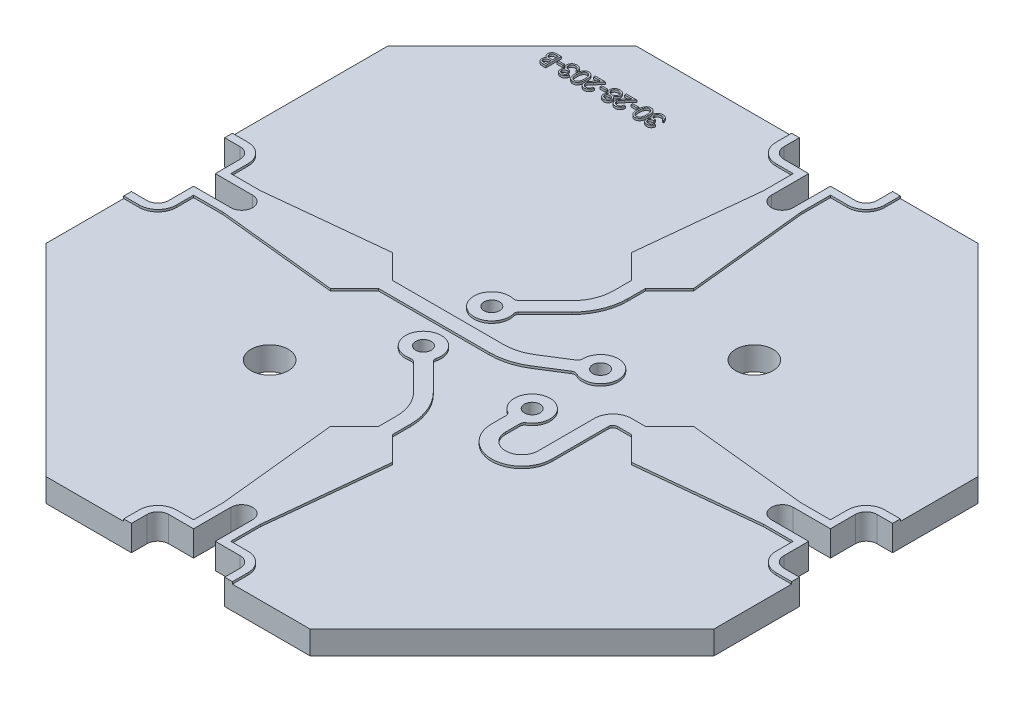
SolidWorks part; units mm, degrees
ref_plane "Front Plane" through (0, 0, 0) normal (0, 0, 1) x (1, 0, 0)
ref_plane "Top Plane" through (0, 0, 0) normal (0, 1, 0) x (1, 0, 0)
ref_plane "Right Plane" through (0, 0, 0) normal (1, 0, 0) x (0, 0, -1)
sketch "Sketch1" plane through (0, 0, 0) normal (0, 1, 0) x (1, 0, 0)
  line L0 (0, 5.461) -> (0, -5.461) construction
  line L1 (-5.461, 3.429) -> (-5.461, 0.762)
  line L2 (-3.429, 5.461) -> (-0.762, 5.461)
  line L3 (5.461, 2.159) -> (5.461, 0.762)
  line L4 (-2.159, -5.461) -> (-0.762, -5.461)
  line L5 (5.461, 0) -> (-5.461, 0) construction
  line L6 (2.159, 5.461) -> (5.461, 2.159)
  line L7 (2.159, -5.461) -> (5.461, -2.159)
  line L8 (-5.461, -2.159) -> (-2.159, -5.461)
  line L9 (-5.461, 3.429) -> (-3.429, 5.461)
  line L10 (-0.5842, 5.0292) -> (-0.1778, 5.0292)
  line L11 (0.762, 5.461) -> (2.159, 5.461)
  line L12 (-0.762, 5.207) -> (-0.762, 5.461)
  line L13 (-0.762, -5.461) -> (-0.762, -5.207)
  line L14 (0.762, 5.207) -> (0.762, 5.461)
  line L15 (0.762, -5.461) -> (0.762, -5.207)
  line L16 (-1.8926, 0) -> (-1.8926, -1.9812) construction
  line L17 (0.762, -5.461) -> (2.159, -5.461)
  line L18 (-1.8926, -1.9812) -> (-3.429, -1.9812) construction
  line L19 (2.032, 0) -> (2.032, 1.9812) construction
  line L20 (2.032, 1.9812) -> (0.762, 1.9812) construction
  line L21 (5.461, -0.762) -> (5.461, -2.159)
  line L24 (0, 0) -> (-2.667, -2.667) construction
  line L25 (0, 0) -> (2.667, 2.667) construction
  line L27 (-5.461, -0.762) -> (-5.461, -2.159)
  line L28 (0.1778, 4.4196) -> (0.1778, 5.0292)
  line L29 (-0.1778, 4.4196) -> (-0.1778, 5.0292)
  line L30 (0.1778, 5.0292) -> (0.5842, 5.0292)
  line L34 (5.207, 0.762) -> (5.461, 0.762)
  line L35 (5.207, -0.762) -> (5.461, -0.762)
  line L36 (4.4196, -0.1778) -> (5.0292, -0.1778)
  line L37 (5.0292, -0.5842) -> (5.0292, -0.1778)
  line L38 (4.4196, 0.1778) -> (5.0292, 0.1778)
  line L39 (5.0292, 0.1778) -> (5.0292, 0.5842)
  line L40 (-5.0292, 0.1778) -> (-5.0292, 0.5842)
  line L41 (-4.4196, 0.1778) -> (-5.0292, 0.1778)
  line L42 (-5.0292, -0.5842) -> (-5.0292, -0.1778)
  line L43 (-4.4196, -0.1778) -> (-5.0292, -0.1778)
  line L44 (-5.207, -0.762) -> (-5.461, -0.762)
  line L45 (-5.207, 0.762) -> (-5.461, 0.762)
  line L46 (-2.667, 2.667) -> (2.667, 2.667) construction
  line L47 (-2.667, 2.667) -> (-2.667, -2.667) construction
  line L48 (-2.667, -2.667) -> (2.667, -2.667) construction
  line L49 (0.5842, -5.0292) -> (0.1778, -5.0292)
  line L52 (2.667, 2.667) -> (2.667, -2.667) construction
  line L53 (-0.1778, -4.4196) -> (-0.1778, -5.0292)
  line L54 (0.1778, -4.4196) -> (0.1778, -5.0292)
  line L55 (-0.1778, -5.0292) -> (-0.5842, -5.0292)
  circle A0 centre (0.889, 0.5588) radius 0.127
  circle A1 centre (0.889, -0.5588) radius 0.127
  circle A2 centre (-0.889, -0.5588) radius 0.127
  circle A3 centre (-0.889, 0.5588) radius 0.127
  arc A4 (-0.1778, 4.4196) -> (0.1778, 4.4196) centre (0, 4.4196) ccw
  arc A5 (-0.5842, 5.0292) -> (-0.762, 5.207) centre (-0.5842, 5.207) cw
  arc A6 (-0.762, -5.207) -> (-0.5842, -5.0292) centre (-0.5842, -5.207) cw
  arc A7 (0.1778, -4.4196) -> (-0.1778, -4.4196) centre (0, -4.4196) ccw
  arc A8 (0.762, -5.207) -> (0.5842, -5.0292) centre (0.5842, -5.207) ccw
  circle A9 centre (-1.9812, -1.9812) radius 0.3048
  circle A10 centre (1.9812, 1.9812) radius 0.3048
  arc A11 (5.207, 0.762) -> (5.0292, 0.5842) centre (5.207, 0.5842) ccw
  arc A12 (0.762, 5.207) -> (0.5842, 5.0292) centre (0.5842, 5.207) cw
  arc A14 (4.4196, -0.1778) -> (4.4196, 0.1778) centre (4.4196, 0) cw
  arc A15 (5.0292, -0.5842) -> (5.207, -0.762) centre (5.207, -0.5842) ccw
  arc A16 (-5.0292, -0.5842) -> (-5.207, -0.762) centre (-5.207, -0.5842) cw
  arc A18 (-4.4196, -0.1778) -> (-4.4196, 0.1778) centre (-4.4196, 0) ccw
  arc A20 (-5.207, 0.762) -> (-5.0292, 0.5842) centre (-5.207, 0.5842) cw
  point P0 (5.461, -5.461)
  point P1 (-5.461, -5.461)
  point P2 (-5.461, 5.461)
  point P3 (5.461, 5.461)
  point P67 (-0.762, 5.0292)
  point P70 (0.762, 5.0292)
  dimension "D3" = 0.1778
  dimension "D4" = 1.9812
  dimension "D9" = 1.9812
  dimension "D1" = 10.922
  dimension "D2" = 10.922
  dimension "D5" = 3.302
  dimension "D6" = 3.302
  dimension "D7" = 3.302
  dimension "D8" = 2.032
extrude "Substrate" add sketch "Sketch1" along normal blind 0.381
sketch "Sketch3" plane through (0, 0, 0) normal (0, -1, 0) x (1, 0, 0)
  line L1 (-2.667, -2.667) -> (2.667, -2.667)
  line L2 (-2.667, -2.667) -> (-2.667, 2.667)
  line L3 (-2.667, 2.667) -> (2.667, 2.667)
  line L4 (2.667, -2.667) -> (2.667, 2.667)
  line L6 (-2.667, 0) -> (2.667, 0) construction
  line L7 (0, 2.667) -> (0, -2.667) construction
  circle A0 centre (0.889, -0.5588) radius 0.4064
  circle A1 centre (-0.889, -0.5588) radius 0.4064
  circle A2 centre (-0.889, 0.5588) radius 0.4064
  circle A3 centre (0.889, 0.5588) radius 0.4064
  circle A4 centre (1.9812, -1.9812) radius 0.3048
  circle A5 centre (-1.9812, 1.9812) radius 0.3048
  circle A16 centre (0, 0) radius 2.159 construction
extrude "Bottom trace" add sketch "Sketch3" along normal blind 0.0025
sketch "Sketch5" plane through (0, 0.381, 0) normal (0, 1, 0) x (-1, 0, 0)
  line L0 (-1.8415, -0.1143) -> (-2.0702, -0.1143)
  line L1 (-0.762, 5.207) -> (-0.9756, 5.207) construction
  line L2 (-0.762, 5.461) -> (-0.889, 5.461)
  line L3 (-0.762, 5.461) -> (-0.762, 5.207)
  line L4 (-0.889, 5.461) -> (-0.889, 5.207)
  line L5 (-1.8415, 0.1143) -> (-2.0702, 0.1143)
  line L6 (-1.651, 1.1087) -> (-1.651, 0.1905) construction
  line L7 (-1.8415, 0) -> (-2.667, 0) construction
  line L8 (2.667, 0) -> (0.254, 0) construction
  line L9 (0.1778, 4.4196) -> (0.4683, 4.4196) construction
  line L10 (0.1778, 5.0292) -> (0.3048, 4.9022) construction
  line L11 (-0.5842, 5.0292) -> (-0.5842, 4.7102) construction
  line L12 (-0.762, -5.207) -> (-0.762, -5.461)
  line L13 (-0.215, -0.1352) -> (-0.889, -0.5588) construction
  line L14 (0, -2.667) -> (0, -1.778) construction
  line L15 (2.667, -2.667) -> (-2.667, -2.667) construction
  line L16 (0.7972, -1.778) -> (0.0607, -1.4729) construction
  line L17 (0.1527, -1.1335) -> (0.5888, -0.6973)
  line L18 (0.762, 5.207) -> (1.0719, 5.207) construction
  line L19 (0.5842, 5.0292) -> (0.5842, 4.7462) construction
  line L20 (0.3143, -1.2951) -> (0.739, -0.8704)
  line L21 (0.6825, -0.7653) -> (0.2335, -1.2143) construction
  line L22 (0.1143, -2.0702) -> (0.1143, -1.778)
  line L23 (0.9505, 1.114) -> (0.2996, 0.3642) construction
  line L24 (-0.1143, -2.0702) -> (-0.1143, -1.778)
  line L25 (-0.1778, 5.0292) -> (-0.3048, 4.9022) construction
  line L26 (0.6825, 0.7653) -> (0.2335, 1.2143) construction
  line L27 (0.9505, -1.114) -> (0.2996, -0.3642) construction
  line L28 (0.7972, 1.778) -> (0.0607, 1.4729) construction
  line L29 (-0.2759, -0.0384) -> (-0.6776, -0.2909)
  line L30 (0.5079, -2.4638) -> (0.1143, -2.0702)
  line L31 (-0.5079, -2.4638) -> (-0.1143, -2.0702)
  line L32 (-0.889, 0.5588) -> (-0.889, 1.1087) construction
  line L33 (-0.5079, 2.4638) -> (-0.1143, 2.0702)
  line L34 (0.5079, 2.4638) -> (0.1143, 2.0702)
  line L35 (-0.1143, 2.0702) -> (-0.1143, 1.778)
  line L36 (0.762, 5.0292) -> (0.9652, 4.826) construction
  line L37 (0.1143, 2.0702) -> (0.1143, 1.778)
  line L38 (0.3143, 1.2951) -> (0.739, 0.8704)
  line L39 (0.1527, 1.1335) -> (0.5888, 0.6973)
  line L40 (-0.1542, -0.2319) -> (-0.5625, -0.4886)
  line L41 (0.254, 0.1143) -> (2.0702, 0.1143)
  line L42 (0.254, -0.1143) -> (2.0702, -0.1143)
  line L43 (2.4638, -0.5079) -> (2.0702, -0.1143)
  line L44 (2.4638, 0.5079) -> (2.0702, 0.1143)
  line L45 (-2.4638, 0.5079) -> (-2.0702, 0.1143)
  line L46 (-2.4638, -0.5079) -> (-2.0702, -0.1143)
  line L47 (-1.143, 1.4224) -> (-1.397, 1.4224) construction
  line L48 (-0.7747, 0.8763) -> (-0.7747, 1.1087)
  line L49 (-0.4899, -0.6131) -> (-0.743, -0.1788) construction
  line L50 (-0.5969, 0.8763) -> (-1.143, 0.8763) construction
  line L51 (-1.0033, 0.8763) -> (-1.0033, 1.1087)
  line L52 (-1.397, 1.3081) -> (-1.143, 1.3081) construction
  line L53 (-1.397, 1.5367) -> (-1.143, 1.5367) construction
  line L54 (-1.5367, 0.1905) -> (-1.5367, 1.1087)
  line L55 (-1.7653, 0.1905) -> (-1.7653, 1.1087)
  line L124 (-0.3048, 4.4196) -> (-0.5079, 2.4638)
  line L125 (0.3048, 4.4196) -> (0.5079, 2.4638)
  line L127 (0.3048, 4.9022) -> (0.3048, 4.4196)
  line L128 (-0.3048, 4.9022) -> (-0.3048, 4.4196)
  line L142 (0.762, -5.0292) -> (0.9652, -4.826) construction
  line L144 (0.5842, -4.9022) -> (0.3048, -4.9022)
  line L145 (-0.1778, -5.0292) -> (-0.3048, -4.9022) construction
  line L160 (-0.5842, 4.9022) -> (-0.3048, 4.9022)
  line L161 (0.5842, 4.9022) -> (0.3048, 4.9022)
  line L162 (0.889, 5.461) -> (0.889, 5.207)
  line L163 (-0.5842, 5.0292) -> (-0.1778, 5.0292)
  line L164 (-0.1778, 4.4196) -> (-0.1778, 5.0292)
  line L165 (0.762, 5.461) -> (0.889, 5.461)
  line L166 (0.1778, 5.0292) -> (0.1778, 4.4196)
  line L167 (0.5842, 5.0292) -> (0.1778, 5.0292)
  line L168 (0.762, 5.461) -> (0.762, 5.207)
  line L169 (0.762, -5.461) -> (0.889, -5.461)
  line L172 (0.762, -5.207) -> (1.0719, -5.207) construction
  line L173 (0.762, -5.461) -> (0.762, -5.207)
  line L176 (0.889, -5.461) -> (0.889, -5.207)
  line L177 (0.762, -5.0292) -> (0.9652, -4.826) construction
  line L178 (0.5842, -5.0292) -> (0.1778, -5.0292)
  line L179 (-0.5842, -5.0292) -> (-0.1778, -5.0292)
  line L180 (-0.1778, -5.0292) -> (-0.3048, -4.9022) construction
  line L181 (-0.5842, -5.0292) -> (-0.5842, -4.7102) construction
  line L182 (-0.1778, -4.4196) -> (-0.1778, -5.0292)
  line L185 (0.5842, -5.0292) -> (0.5842, -4.7462) construction
  line L186 (0.1778, -4.4196) -> (0.4683, -4.4196) construction
  line L187 (-0.889, -5.461) -> (-0.889, -5.207)
  line L188 (0.1778, -5.0292) -> (0.1778, -4.4196)
  line L189 (-0.762, -5.461) -> (-0.889, -5.461)
  line L190 (-0.762, -5.207) -> (-0.9756, -5.207) construction
  line L192 (-0.5842, -4.9022) -> (-0.3048, -4.9022)
  line L193 (0.1778, -5.0292) -> (0.3048, -4.9022) construction
  line L195 (5.461, 0.762) -> (5.461, 0.889)
  line L197 (5.461, -0.762) -> (5.207, -0.762)
  line L198 (5.207, 0.762) -> (5.207, 1.0719) construction
  line L199 (5.461, 0.762) -> (5.207, 0.762)
  line L200 (4.4196, 0.3048) -> (2.4638, 0.5079)
  line L201 (4.9022, 0.5842) -> (4.9022, 0.3048)
  line L202 (5.461, 0.889) -> (5.207, 0.889)
  line L203 (5.0292, 0.762) -> (4.826, 0.9652) construction
  line L204 (5.0292, 0.5842) -> (5.0292, 0.1778)
  line L205 (5.0292, -0.5842) -> (5.0292, -0.1778)
  line L206 (5.0292, -0.1778) -> (4.9022, -0.3048) construction
  line L208 (5.0292, -0.5842) -> (4.7102, -0.5842) construction
  line L210 (4.4196, -0.1778) -> (5.0292, -0.1778)
  line L211 (4.4196, -0.3048) -> (2.4638, -0.5079)
  line L212 (4.9022, -0.3048) -> (4.4196, -0.3048)
  line L213 (5.0292, 0.5842) -> (4.7462, 0.5842) construction
  line L214 (4.4196, 0.1778) -> (4.4196, 0.4683) construction
  line L215 (5.461, -0.889) -> (5.207, -0.889)
  line L216 (5.0292, 0.1778) -> (4.4196, 0.1778)
  line L218 (5.461, -0.762) -> (5.461, -0.889)
  line L219 (5.207, -0.762) -> (5.207, -0.9756) construction
  line L220 (4.9022, 0.3048) -> (4.4196, 0.3048)
  line L221 (4.9022, -0.5842) -> (4.9022, -0.3048)
  line L223 (5.0292, 0.1778) -> (4.9022, 0.3048) construction
  line L228 (-5.0292, 0.1778) -> (-4.9022, 0.3048) construction
  line L229 (-5.207, -0.762) -> (-5.207, -0.9756) construction
  line L230 (-4.4196, 0.1778) -> (-4.4196, 0.4683) construction
  line L231 (-5.0292, 0.5842) -> (-4.7462, 0.5842) construction
  line L232 (-5.0292, -0.5842) -> (-4.7102, -0.5842) construction
  line L234 (-5.0292, -0.1778) -> (-4.9022, -0.3048) construction
  line L235 (-5.0292, 0.762) -> (-4.826, 0.9652) construction
  line L236 (-5.207, 0.762) -> (-5.207, 1.0719) construction
  line L237 (-0.889, -0.5588) -> (-0.762, -0.5588) construction
  line L242 (-4.9022, -0.5842) -> (-4.9022, -0.3048)
  line L244 (-4.9022, 0.3048) -> (-4.4196, 0.3048)
  line L245 (-5.461, -0.762) -> (-5.461, -0.889)
  line L247 (-5.0292, 0.1778) -> (-4.4196, 0.1778)
  line L248 (-5.461, -0.889) -> (-5.207, -0.889)
  line L249 (-4.9022, -0.3048) -> (-4.4196, -0.3048)
  line L250 (-4.4196, -0.3048) -> (-2.4638, -0.5079)
  line L251 (-4.4196, -0.1778) -> (-5.0292, -0.1778)
  line L252 (-5.0292, -0.5842) -> (-5.0292, -0.1778)
  line L253 (-5.0292, 0.5842) -> (-5.0292, 0.1778)
  line L254 (-5.461, 0.889) -> (-5.207, 0.889)
  line L255 (-4.9022, 0.5842) -> (-4.9022, 0.3048)
  line L256 (-4.4196, 0.3048) -> (-2.4638, 0.5079)
  line L257 (-5.461, 0.762) -> (-5.207, 0.762)
  line L258 (-5.461, -0.762) -> (-5.207, -0.762)
  line L260 (-5.461, 0.762) -> (-5.461, 0.889)
  line L286 (-0.3048, -4.9022) -> (-0.3048, -4.4196)
  line L294 (0.5842, -5.0292) -> (0.5842, -4.7462) construction
  line L295 (0.762, -5.207) -> (1.0719, -5.207) construction
  line L296 (-0.762, -5.207) -> (-0.9756, -5.207) construction
  line L297 (-0.5842, -5.0292) -> (-0.5842, -4.7102) construction
  line L298 (0.1778, -5.0292) -> (0.3048, -4.9022) construction
  line L299 (0.3048, -4.9022) -> (0.3048, -4.4196)
  line L300 (0.1778, -4.4196) -> (0.4683, -4.4196) construction
  line L302 (0.3048, -4.4196) -> (0.5079, -2.4638)
  line L303 (-0.3048, -4.4196) -> (-0.5079, -2.4638)
  arc A0 (0.8255, -0.8439) -> (0.6074, -0.6363) centre (0.889, -0.5588) ccw
  arc A1 (0, -1.778) -> (0.2335, -1.2143) centre (0.7972, -1.778) cw construction
  arc A2 (0.1143, -1.778) -> (0.3143, -1.2951) centre (0.7972, -1.778) cw
  arc A3 (0, 1.778) -> (0.2335, 1.2143) centre (0.7972, 1.778) ccw construction
  arc A4 (-0.1143, -1.778) -> (0.1527, -1.1335) centre (0.7972, -1.778) cw
  arc A5 (0.739, -0.8704) -> (0.8255, -0.8439) centre (0.8072, -0.9386) cw
  arc A6 (-0.5842, 4.9022) -> (-0.889, 5.207) centre (-0.5842, 5.207) cw
  arc A7 (-0.5842, 5.0292) -> (-0.762, 5.207) centre (-0.5842, 5.207) cw
  arc A8 (0.254, 0) -> (-0.215, -0.1352) centre (0.254, -0.8814) ccw construction
  arc A9 (0.5888, -0.6973) -> (0.6074, -0.6363) centre (0.5409, -0.6495) ccw
  arc A10 (0.889, 5.207) -> (0.5842, 4.9022) centre (0.5842, 5.207) cw
  circle A11 centre (0.889, -0.5588) radius 0.127
  arc A12 (0.5842, 5.0292) -> (0.762, 5.207) centre (0.5842, 5.207) ccw
  arc A13 (0.1778, 4.4196) -> (-0.1778, 4.4196) centre (0, 4.4196) cw
  arc A14 (0.5842, -5.0292) -> (0.762, -5.207) centre (0.5842, -5.207) cw
  arc A15 (-0.5842, -5.0292) -> (-0.762, -5.207) centre (-0.5842, -5.207) ccw
  circle A16 centre (0.889, 0.5588) radius 0.127
  arc A17 (0.889, -5.207) -> (0.5842, -4.9022) centre (0.5842, -5.207) ccw
  arc A18 (0.5888, 0.6973) -> (0.6074, 0.6363) centre (0.5409, 0.6495) cw
  arc A19 (-0.5842, -4.9022) -> (-0.889, -5.207) centre (-0.5842, -5.207) ccw
  arc A20 (0.1778, -4.4196) -> (-0.1778, -4.4196) centre (0, -4.4196) ccw
  arc A21 (5.0292, 0.5842) -> (5.207, 0.762) centre (5.207, 0.5842) cw
  arc A22 (5.0292, -0.5842) -> (5.207, -0.762) centre (5.207, -0.5842) ccw
  arc A23 (5.207, 0.889) -> (4.9022, 0.5842) centre (5.207, 0.5842) ccw
  arc A24 (4.9022, -0.5842) -> (5.207, -0.889) centre (5.207, -0.5842) ccw
  arc A25 (4.4196, 0.1778) -> (4.4196, -0.1778) centre (4.4196, 0) ccw
  arc A26 (-4.4196, 0.1778) -> (-4.4196, -0.1778) centre (-4.4196, 0) cw
  arc A27 (-4.9022, -0.5842) -> (-5.207, -0.889) centre (-5.207, -0.5842) cw
  arc A28 (-5.207, 0.889) -> (-4.9022, 0.5842) centre (-5.207, 0.5842) cw
  arc A29 (-5.0292, -0.5842) -> (-5.207, -0.762) centre (-5.207, -0.5842) cw
  arc A30 (-5.0292, 0.5842) -> (-5.207, 0.762) centre (-5.207, 0.5842) ccw
  arc A31 (0.739, 0.8704) -> (0.8255, 0.8439) centre (0.8072, 0.9386) ccw
  arc A32 (-0.1143, 1.778) -> (0.1527, 1.1335) centre (0.7972, 1.778) ccw
  arc A33 (0.1143, 1.778) -> (0.3143, 1.2951) centre (0.7972, 1.778) ccw
  circle A34 centre (-0.889, -0.5588) radius 0.127 construction
  circle A35 centre (-0.889, -0.5588) radius 0.127
  arc A36 (0.8255, 0.8439) -> (0.6074, 0.6363) centre (0.889, 0.5588) cw
  arc A37 (0.254, 0.1143) -> (-0.2759, -0.0384) centre (0.254, -0.8814) ccw
  arc A38 (0.254, -0.1143) -> (-0.1542, -0.2319) centre (0.254, -0.8814) ccw
  arc A39 (-0.7539, -0.2998) -> (-0.5971, -0.5472) centre (-0.889, -0.5588) ccw
  arc A40 (-0.5625, -0.4886) -> (-0.5971, -0.5472) centre (-0.5229, -0.5515) ccw
  arc A41 (-0.6776, -0.2909) -> (-0.7539, -0.2998) centre (-0.7251, -0.2154) cw
  arc A42 (-1.8415, 0) -> (-1.651, 0.1905) centre (-1.8415, 0.1905) ccw construction
  arc A43 (-1.8415, -0.1143) -> (-1.5367, 0.1905) centre (-1.8415, 0.1905) ccw
  arc A44 (-1.8415, 0.1143) -> (-1.7653, 0.1905) centre (-1.8415, 0.1905) ccw
  arc A45 (-1.651, 1.1684) -> (-1.397, 1.4224) centre (-1.397, 1.1684) cw construction
  arc A46 (-1.143, 1.4224) -> (-0.889, 1.1684) centre (-1.143, 1.1684) cw construction
  circle A47 centre (-0.889, 0.5588) radius 0.127
  arc A48 (-1.5367, 1.1684) -> (-1.397, 1.3081) centre (-1.397, 1.1684) cw construction
  arc A49 (-1.7653, 1.1684) -> (-1.397, 1.5367) centre (-1.397, 1.1684) cw construction
  arc A50 (-1.143, 1.3081) -> (-1.0033, 1.1684) centre (-1.143, 1.1684) cw construction
  arc A51 (-1.143, 1.5367) -> (-0.7747, 1.1684) centre (-1.143, 1.1684) cw construction
  arc A52 (-1.0351, 0.8118) -> (-0.743, 0.8118) centre (-0.889, 0.5588) ccw
  arc A53 (-1.0033, 0.8763) -> (-1.0351, 0.8118) centre (-1.0848, 0.8763) cw
  arc A54 (-0.7747, 0.8763) -> (-0.743, 0.8118) centre (-0.6932, 0.8763) ccw
  arc A55 (-1.651, 1.1087) -> (-0.889, 1.1087) centre (-1.27, 1.1087) cw construction
  arc A56 (-1.5367, 1.1087) -> (-1.0033, 1.1087) centre (-1.27, 1.1087) cw
  arc A57 (-1.7653, 1.1087) -> (-0.7747, 1.1087) centre (-1.27, 1.1087) cw
  text T0 "30-28-203-B\r\n" font "Century Gothic" height 0.254
  dimension "D2" = 0.1143
  dimension "D4" = 0.2286
  dimension "D5" = 0.1143
  dimension "D6" = 0.1143
  dimension "D7" = 0.1143
  dimension "D10" = 0.1143
  dimension "D11" = 0.1143
  dimension "D12" = 0.1143
  dimension "D3" = 0.1143
  dimension "D8" = 0.1143
  dimension "D9" = 0.1143
extrude "Top trace" add sketch "Sketch5" along normal blind 0.0356
